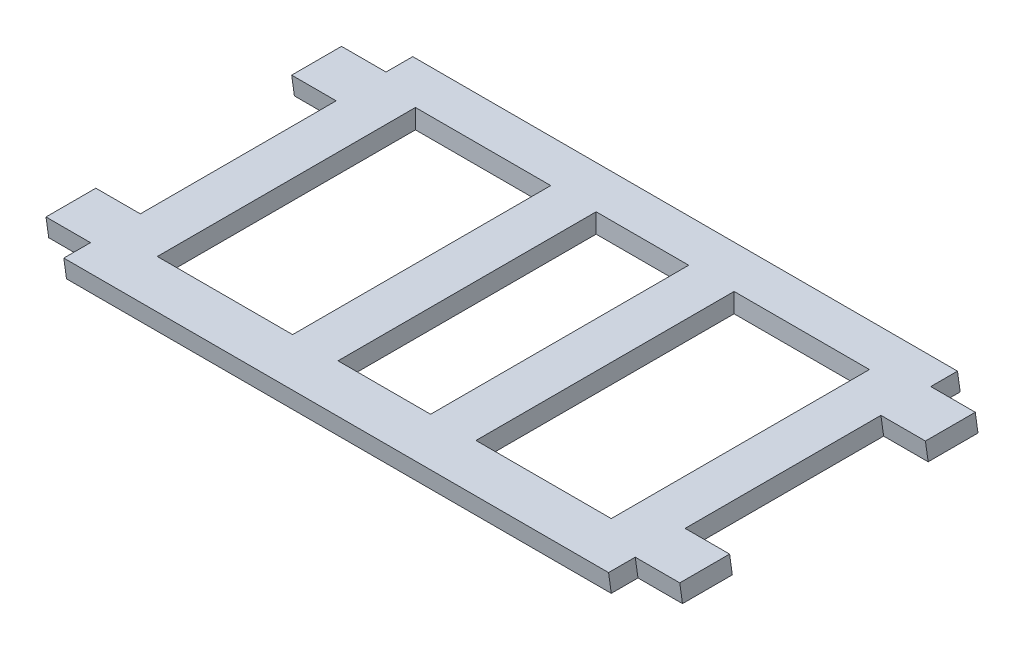
SolidWorks part; units mm, degrees
material "Balsa"
ref_plane "Front Plane" through (0, 0, 0) normal (0, 0, 1) x (1, 0, 0)
ref_plane "Top Plane" through (0, 0, 0) normal (0, 1, 0) x (1, 0, 0)
ref_plane "Right Plane" through (0, 0, 0) normal (1, 0, 0) x (0, 0, -1)
sketch "Sketch1" plane through (0, 0, 0) normal (0, 1, 0) x (1, 0, 0)
  line L4 (0, 0) -> (0, 7.112) construction
  line L5 (0, 7.112) -> (6.35, 7.112)
  line L6 (6.35, 7.112) -> (6.35, 35.052)
  line L7 (6.35, 35.052) -> (0, 35.052)
  line L8 (0, 7.112) -> (0, 0)
  line L10 (6.35, 7.112) -> (84.074, 7.112) construction
  line L11 (84.074, 7.112) -> (90.424, 7.112)
  line L12 (84.074, 7.112) -> (84.074, 35.052)
  line L13 (84.074, 35.052) -> (90.424, 35.052)
  line L15 (90.424, 7.112) -> (90.424, 0)
  line L16 (0, 35.052) -> (0, 42.164)
  line L18 (90.424, 42.164) -> (90.424, 35.052)
  line L19 (0, 42.164) -> (6.35, 42.164)
  line L20 (6.35, 42.164) -> (6.35, 45.974)
  line L21 (90.424, 42.164) -> (84.074, 42.164)
  line L22 (84.074, 42.164) -> (84.074, 45.974)
  line L23 (6.35, 45.974) -> (84.074, 45.974)
  line L24 (0, 0) -> (6.35, 0)
  line L25 (6.35, 0) -> (6.35, -3.81)
  line L26 (90.424, 0) -> (84.074, 0)
  line L27 (84.074, 0) -> (84.074, -3.81)
  line L28 (6.35, -3.81) -> (84.074, -3.81)
  dimension "D1" = 7.112
  dimension "D2" = 90.424
  dimension "D3" = 6.35
  dimension "D4" = 27.94
  dimension "D5" = 77.724
  dimension "D6" = 6.35
  dimension "D7" = 27.94
  dimension "D8" = 7.112
  dimension "D9" = 6.35
  dimension "D10" = 3.81
  dimension "D11" = 6.35
  dimension "D12" = 3.81
  dimension "D13" = 6.35
  dimension "D14" = 3.81
  dimension "D15" = 6.35
  dimension "D16" = 3.81
ref_plane "Plane1" through (0, 2.7668, 0) normal (0, 1, 0) x (1, 0, 0)
sketch "Sketch2" plane through (0, 2.7668, 0) normal (0, 1, 0) x (1, 0, 0)
  line L0 (0, 0) -> (0, -0.3888) construction
  line L2 (90.424, -0.3888) -> (90.424, 6.7232)
  line L3 (90.424, 7.112) -> (90.424, 0) construction
  line L4 (90.424, 6.7232) -> (84.074, 6.7232)
  line L5 (84.074, 6.7232) -> (84.074, 34.6632)
  line L6 (84.074, 7.112) -> (84.074, 35.052) construction
  line L7 (84.074, 34.6632) -> (90.424, 34.6632)
  line L8 (90.424, 34.6632) -> (90.424, 41.7752)
  line L9 (90.424, 42.164) -> (90.424, 35.052) construction
  line L11 (0, 35.052) -> (0, 42.164) construction
  line L12 (0, 41.7752) -> (0, 34.6632)
  line L13 (0, 34.6632) -> (6.35, 34.6632)
  line L14 (6.35, 7.112) -> (6.35, 35.052) construction
  line L15 (6.35, 34.6632) -> (6.35, 6.7232)
  line L16 (6.35, 6.7232) -> (0, 6.7232)
  line L17 (0, 7.112) -> (0, 0) construction
  line L18 (0, 6.7232) -> (0, -0.3888)
  line L19 (0, -0.3888) -> (6.35, -0.3888)
  line L20 (6.35, 0) -> (6.35, -3.81) construction
  line L21 (6.35, -0.3888) -> (6.35, -4.1988)
  line L22 (90.424, -0.3888) -> (84.074, -0.3888)
  line L23 (84.074, 0) -> (84.074, -3.81) construction
  line L24 (84.074, -0.3888) -> (84.074, -4.1988)
  line L25 (6.35, -4.1988) -> (84.074, -4.1988)
  line L26 (0, 41.7752) -> (6.35, 41.7752)
  line L27 (6.35, 41.7752) -> (6.35, 45.5852)
  line L28 (6.35, 42.164) -> (6.35, 45.974) construction
  line L29 (90.424, 41.7752) -> (84.074, 41.7752)
  line L30 (84.074, 41.7752) -> (84.074, 45.5852)
  line L31 (84.074, 42.164) -> (84.074, 45.974) construction
  line L32 (6.35, 45.5852) -> (84.074, 45.5852)
  dimension "D1" = 0.3888
  dimension "D2" = 90.424
  dimension "D3" = 7.112
  dimension "D4" = 6.35
  dimension "D5" = 27.94
  dimension "D6" = 6.35
  dimension "D7" = 7.112
  dimension "D8" = 90.424
  dimension "D9" = 7.112
  dimension "D10" = 6.35
  dimension "D11" = 27.94
  dimension "D12" = 6.35
  dimension "D13" = 7.112
  dimension "D14" = 6.35
  dimension "D15" = 3.81
  dimension "D16" = 6.35
  dimension "D17" = 3.81
  dimension "D18" = 6.35
  dimension "D19" = 3.81
  dimension "D20" = 6.35
  dimension "D21" = 3.81
loft "Loft1" add profiles "Sketch1", "Sketch2"
sketch "Sketch4" plane through (0, 2.7668, 0) normal (0, 1, 0) x (1, 0, 0)
  line L0 (0, 0) -> (90.424, 0) construction
  line L1 (45.212, 0) -> (45.212, 42.164) construction
  line L2 (38.608, 21.082) -> (6.35, 21.082) construction
  line L3 (51.816, 2.667) -> (38.608, 2.667)
  line L4 (51.816, 2.667) -> (51.816, 39.497)
  line L5 (51.816, 39.497) -> (38.608, 39.497)
  line L6 (38.608, 2.667) -> (38.608, 39.497)
  line L7 (51.816, 2.667) -> (38.608, 39.497) construction
  line L8 (51.816, 39.497) -> (38.608, 2.667) construction
  line L9 (51.816, 21.082) -> (84.074, 21.082) construction
  line L10 (32.131, 2.667) -> (12.827, 2.667)
  line L11 (32.131, 2.667) -> (32.131, 39.497)
  line L12 (32.131, 39.497) -> (12.827, 39.497)
  line L13 (12.827, 2.667) -> (12.827, 39.497)
  line L14 (32.131, 2.667) -> (12.827, 39.497) construction
  line L15 (32.131, 39.497) -> (12.827, 2.667) construction
  line L17 (77.597, 2.667) -> (58.293, 2.667)
  line L18 (77.597, 2.667) -> (77.597, 39.497)
  line L19 (77.597, 39.497) -> (58.293, 39.497)
  line L20 (58.293, 2.667) -> (58.293, 39.497)
  line L21 (77.597, 2.667) -> (58.293, 39.497) construction
  line L22 (77.597, 39.497) -> (58.293, 2.667) construction
  point P5 (45.212, 21.082)
  point P12 (22.479, 21.082)
  point P19 (67.945, 21.082)
  dimension "D1" = 90.424
  dimension "D2" = 42.164
  dimension "D3" = 36.83
  dimension "D4" = 13.208
  dimension "D5" = 32.258
  dimension "D6" = 19.304
  dimension "D7" = 36.83
  dimension "D8" = 32.258
  dimension "D9" = 19.304
  dimension "D10" = 36.83
extrude "Cut-Extrude1" cut sketch "Sketch4" against normal blind 7.62
